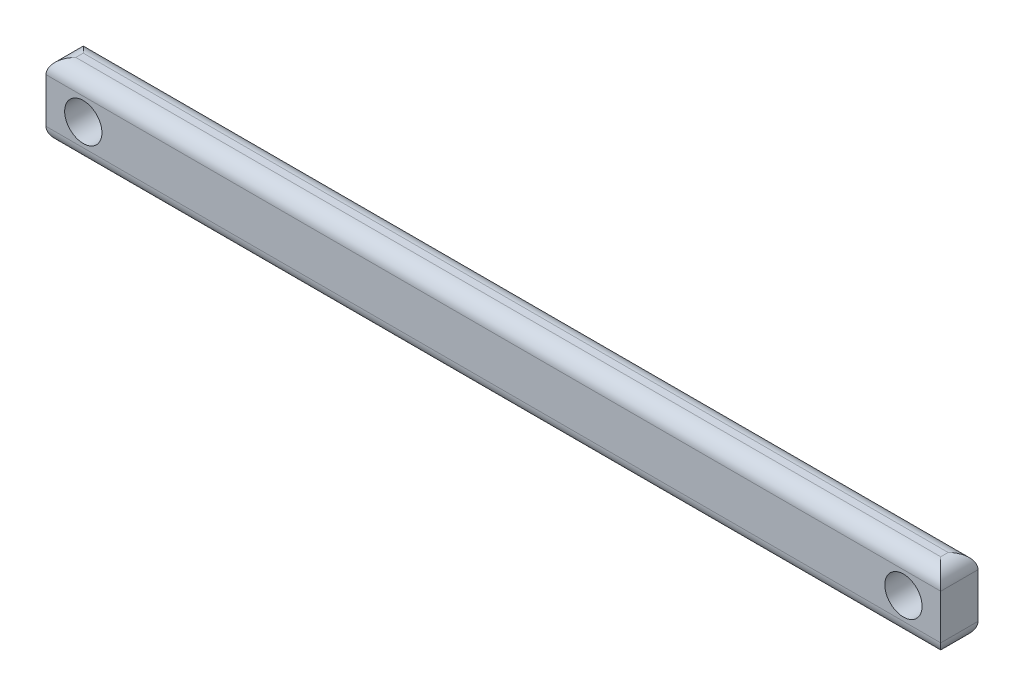
SolidWorks part; units mm, degrees
ref_plane "Front Plane" through (0, 0, 0) normal (0, 0, 1) x (1, 0, 0)
ref_plane "Top Plane" through (0, 0, 0) normal (0, 1, 0) x (1, 0, 0)
ref_plane "Right Plane" through (0, 0, 0) normal (1, 0, 0) x (0, 0, -1)
sketch "Sketch1" plane through (0, 0, 0) normal (0, 0, 1) x (1, 0, 0)
  line L1 (0, 0) -> (-600, 0)
  line L2 (0, 0) -> (0, 50)
  line L3 (0, 50) -> (-600, 50)
  line L4 (-600, 0) -> (-600, 50)
  circle A0 centre (-575, 25) radius 12.5
  circle A1 centre (-25, 25) radius 12.5
  dimension "D3" = 25
  dimension "D4" = 25
  dimension "D1" = 50
  dimension "D2" = 600
  dimension "D5" = 25
  dimension "D6" = 25
extrude "Boss-Extrude2" add sketch "Sketch1" along normal blind 25
fillet "Fillet2" radius 10 8 edges at (-600, 50, 12.5) (-600, 0, 12.5) (0, 0, 12.5) (0, 50, 12.5) (-300, 0, 0) (-300, 50, 0) (-300, 0, 25) (-300, 50, 25)
